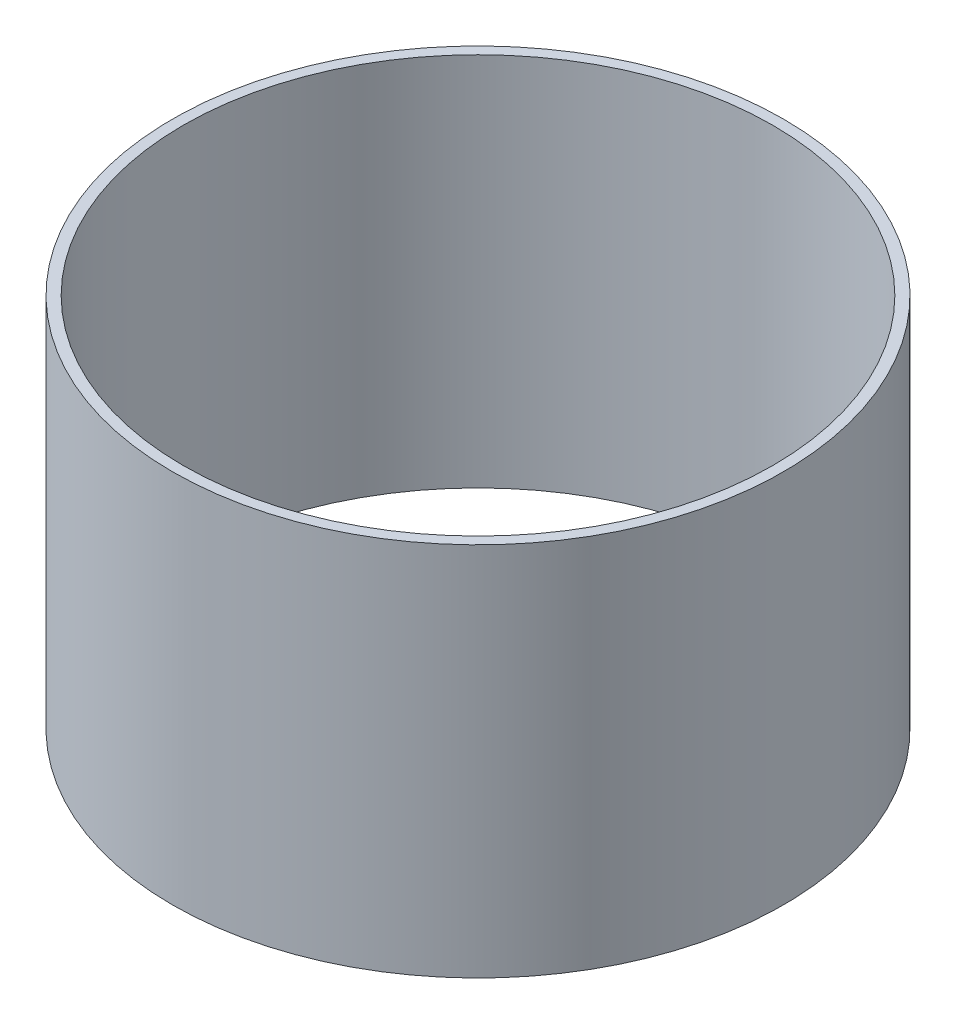
SolidWorks part; units mm, degrees
ref_plane "Front Plane" through (0, 0, 0) normal (0, 0, 1) x (1, 0, 0)
ref_plane "Top Plane" through (0, 0, 0) normal (0, 1, 0) x (1, 0, 0)
ref_plane "Right Plane" through (0, 0, 0) normal (1, 0, 0) x (0, 0, -1)
sketch "Sketch1" plane through (0, 0, 0) normal (0, 1, 0) x (1, 0, 0)
  circle A0 centre (0, 0) radius 55
  circle A1 centre (0, 0) radius 57
  dimension "D1" = 110
  dimension "D2" = 2
extrude "Boss-Extrude1" add sketch "Sketch1" along normal blind 70
sketch "Sketch2" plane through (-168.9329, 99.4365, -468.1144) normal (0, 0, 1) x (1, 0, 0)
  line L0 (111.9329, -29.4365) -> (111.9329, -99.4365) construction
  line L1 (111.9329, 150.5635) -> (225.9329, 150.5635) construction
  line L2 (111.9329, 150.5635) -> (111.9329, 50.5635) construction
  line L3 (111.9329, 50.5635) -> (225.9329, 50.5635) construction
  line L4 (225.9329, 150.5635) -> (225.9329, 50.5635) construction
  line L5 (225.9329, -99.4365) -> (225.9329, -29.4365) construction
  line L6 (118.9329, 143.5635) -> (118.9329, 57.5635)
  line L7 (118.9329, 57.5635) -> (218.9329, 57.5635)
  line L8 (218.9329, 143.5635) -> (218.9329, 57.5635)
  line L9 (118.9329, 143.5635) -> (218.9329, 143.5635)
  line L10 (111.9329, -99.4365) -> (225.9329, -99.4365) construction
  dimension "D2" = 250
  dimension "D3" = 100
  dimension "D1" = 7
